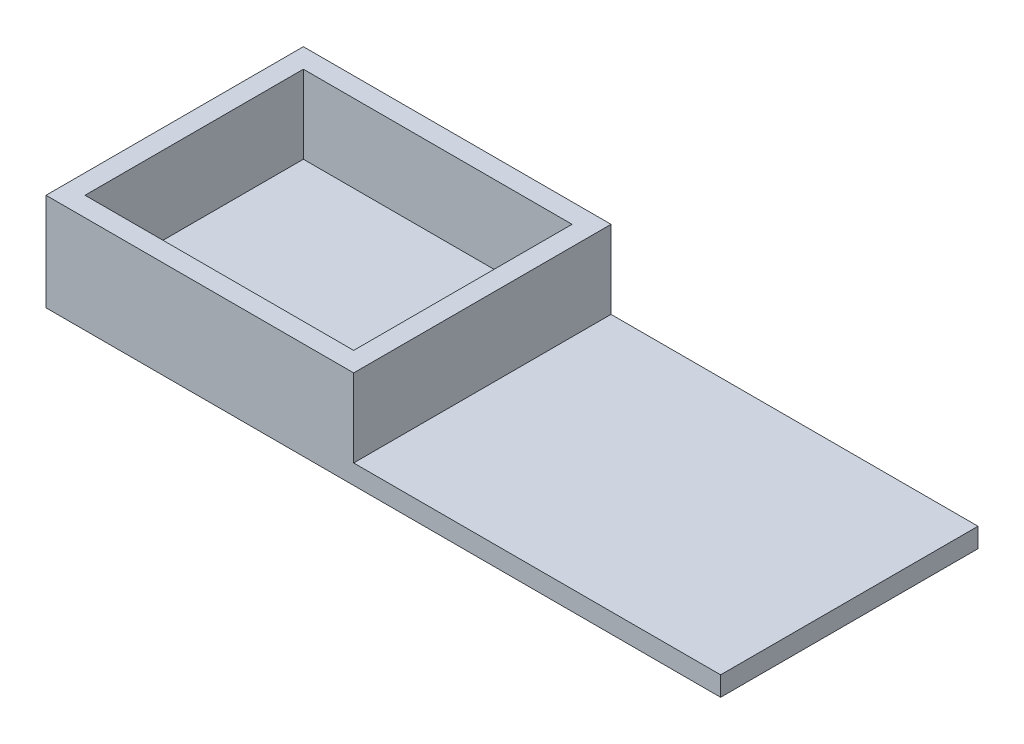
SolidWorks part; units mm, degrees
ref_plane "Front" through (0, 0, 0) normal (0, 0, 1) x (1, 0, 0)
ref_plane "Top" through (0, 0, 0) normal (0, 1, 0) x (1, 0, 0)
ref_plane "Right" through (0, 0, 0) normal (1, 0, 0) x (0, 0, -1)
sketch "Sketch1" plane through (0, 0, 0) normal (0, 1, 0) x (1, 0, 0)
  line L1 (-86.5, -33) -> (86.5, -33)
  line L2 (-86.5, -33) -> (-86.5, 33)
  line L3 (-86.5, 33) -> (86.5, 33)
  line L4 (86.5, -33) -> (86.5, 33)
  line L5 (-86.5, -33) -> (86.5, 33) construction
  line L6 (-86.5, 33) -> (86.5, -33) construction
  point P0 (0, 0)
  dimension "D1" = 173
  dimension "D2" = 66
extrude "Boss-Extrude1" add sketch "Sketch1" along normal blind 5
sketch "Sketch3" plane through (0, 5, 0) normal (0, 1, 0) x (1, 0, 0)
  line L1 (-7.6, -33) -> (-86.5, -33)
  line L2 (-7.6, -33) -> (-7.6, 33)
  line L3 (-7.6, 33) -> (-86.5, 33)
  line L4 (-86.5, -33) -> (-86.5, 33)
  line L5 (-7.6, -33) -> (-86.5, 33) construction
  line L6 (-7.6, 33) -> (-86.5, -33) construction
  point P0 (-47.05, 0)
  dimension "D1" = 78.9
extrude "Boss-Extrude2" add sketch "Sketch3" along normal blind 20
shell "Shell1" thickness 5
